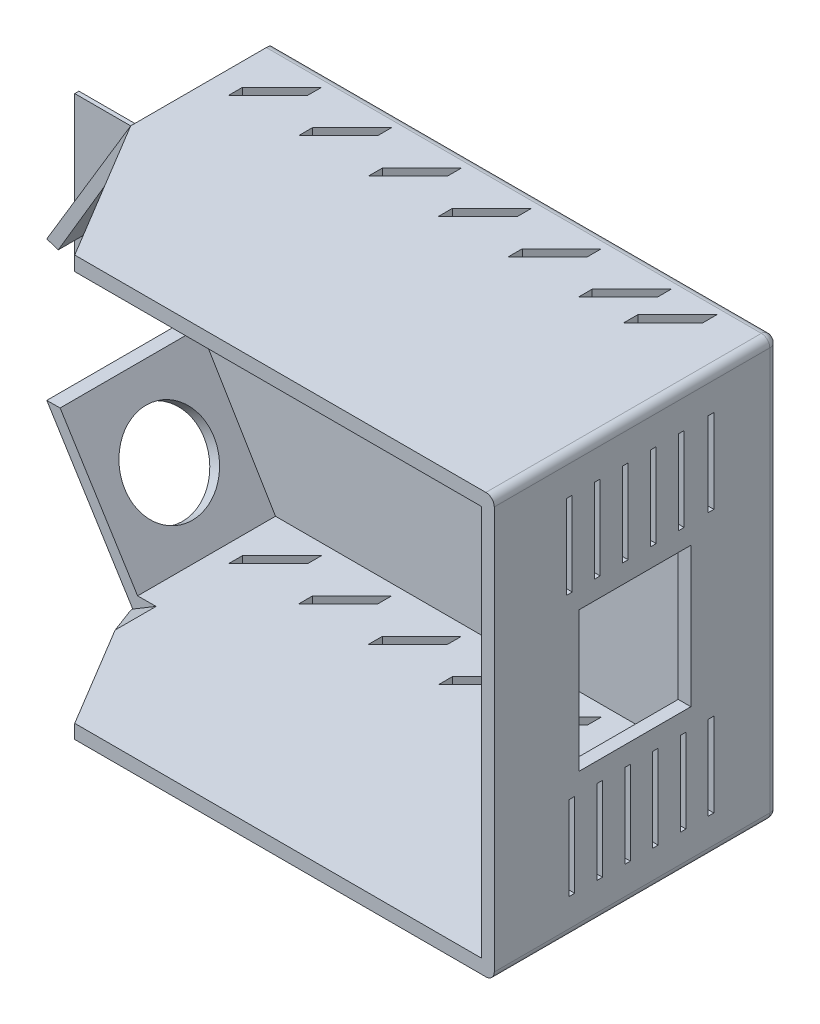
SolidWorks part; units mm, degrees
ref_plane "前视基准面" through (0, 0, 0) normal (0, 0, 1) x (1, 0, 0)
ref_plane "上视基准面" through (0, 0, 0) normal (0, 1, 0) x (1, 0, 0)
ref_plane "右视基准面" through (0, 0, 0) normal (1, 0, 0) x (0, 0, -1)
sketch "草图1" plane through (0, 0, 0) normal (0, 0, 1) x (1, 0, 0)
  line L1 (-53.7975, 24.9859) -> (196.2025, 24.9859)
  line L2 (-53.7975, 24.9859) -> (-53.7975, -125.0141)
  line L3 (-53.7975, -125.0141) -> (196.2025, -125.0141)
  line L4 (196.2025, 24.9859) -> (196.2025, -125.0141)
  dimension "D1" = 250
  dimension "D2" = 150
extrude "凸台-拉伸1" add sketch "草图1" along normal blind 1.5
sketch "草图2" plane through (0, 0, 1.5) normal (0, 0, 1) x (1, 0, 0)
  line L0 (-53.7975, -25.0141) -> (-13.7975, -25.0141)
  line L1 (-53.7975, 24.9859) -> (-53.7975, -125.0141) construction
  line L2 (-13.7975, -25.0141) -> (-13.7975, 24.9859)
  line L3 (196.2025, 24.9859) -> (-53.7975, 24.9859) construction
  line L4 (-13.7975, 24.9859) -> (-53.7975, 24.9859)
  line L5 (-53.7975, 24.9859) -> (-53.7975, -25.0141)
  dimension "D1" = 40
  dimension "D2" = 50
extrude "切除-拉伸1" cut sketch "草图2" against normal through all
sketch "草图3" plane through (0, 0, 1.5) normal (0, 0, 1) x (1, 0, 0)
  line L0 (-53.7975, -75.0141) -> (-13.7975, -75.0141)
  line L1 (-53.7975, -25.0141) -> (-53.7975, -125.0141) construction
  line L2 (-13.7975, -75.0141) -> (-13.7975, -125.0141)
  line L3 (-53.7975, -125.0141) -> (196.2025, -125.0141) construction
  line L4 (-13.7975, -125.0141) -> (-53.7975, -125.0141)
  line L5 (-53.7975, -125.0141) -> (-53.7975, -75.0141)
  dimension "D1" = 40
  dimension "D2" = 50
extrude "切除-拉伸2" cut sketch "草图3" against normal through all
sketch "草图4" plane through (0, 0, 1.5) normal (0, 0, 1) x (1, 0, 0)
  line L0 (-13.7975, -75.0141) -> (16.2025, -125.0141)
  line L1 (-13.7975, -125.0141) -> (196.2025, -125.0141) construction
  line L2 (16.2025, -125.0141) -> (-13.7975, -125.0141)
  line L3 (-13.7975, -75.0141) -> (-13.7975, -125.0141)
  line L4 (-13.7975, -25.0141) -> (16.2025, 24.9859)
  line L5 (196.2025, 24.9859) -> (-13.7975, 24.9859) construction
  line L6 (16.2025, 24.9859) -> (-13.7975, 24.9859)
  line L7 (-13.7975, 24.9859) -> (-13.7975, -25.0141)
  dimension "D1" = 30
  dimension "D2" = 30
extrude "切除-拉伸3" cut sketch "草图4" against normal through all
sketch "草图5" plane through (0, 0, 1.5) normal (0, 0, 1) x (1, 0, 0)
  line L0 (16.2025, -125.0141) -> (196.2025, -125.0141) construction
  line L1 (46.2025, -65.0141) -> (146.2025, -65.0141)
  line L2 (46.2025, -65.0141) -> (46.2025, -55.0141)
  line L3 (46.2025, -55.0141) -> (146.2025, -55.0141)
  line L4 (146.2025, -65.0141) -> (146.2025, -55.0141)
  line L6 (196.2025, -125.0141) -> (196.2025, 24.9859) construction
  line L7 (196.2025, 24.9859) -> (16.2025, 24.9859) construction
  line L8 (46.2025, -45.0141) -> (146.2025, -45.0141)
  line L9 (46.2025, -45.0141) -> (46.2025, -35.0141)
  line L10 (46.2025, -35.0141) -> (146.2025, -35.0141)
  line L11 (146.2025, -45.0141) -> (146.2025, -35.0141)
  dimension "D1" = 60
  dimension "D2" = 100
  dimension "D3" = 50
  dimension "D4" = 100
  dimension "D5" = 10
  dimension "D6" = 10
  dimension "D7" = 60
  dimension "D8" = 50
extrude "切除-拉伸4" cut sketch "草图5" against normal through all
sketch "草图6" plane through (0, 0, 1.5) normal (0, 0, 1) x (1, 0, 0)
  line L0 (-13.7975, -75.0141) -> (-9.0611, -75.0141)
  line L1 (-9.0611, -75.0141) -> (17.9752, -120.0105)
  line L2 (17.9752, -120.0105) -> (191.673, -120.0105)
  line L3 (191.673, -120.0105) -> (191.673, 24.9859)
  line L4 (196.2025, 24.9859) -> (16.2025, 24.9859) construction
  line L5 (191.673, 24.9859) -> (196.2025, 24.9859)
  line L6 (196.2025, 24.9859) -> (196.2025, -125.0141)
  line L7 (196.2025, -125.0141) -> (16.2025, -125.0141)
  line L8 (16.2025, -125.0141) -> (-13.7975, -75.0141)
extrude "凸台-拉伸2" add sketch "草图6" along normal blind 100
sketch "草图7" plane through (0, 0, 1.5) normal (0, 0, 1) x (1, 0, 0)
  line L0 (-9.7019, -26.3734) -> (17.6391, 19.8458)
  line L1 (17.6391, 19.8458) -> (191.673, 19.8458)
  line L2 (191.673, 24.9859) -> (191.673, -120.0105) construction
  line L3 (191.673, 19.8458) -> (191.673, 24.9859)
  line L4 (191.673, 24.9859) -> (16.2025, 24.9859)
  line L5 (16.2025, 24.9859) -> (-13.7975, -25.0141)
  line L6 (-13.7975, -25.0141) -> (-9.7019, -26.3734)
extrude "凸台-拉伸3" add sketch "草图7" along normal blind 100
sketch "草图8" plane through (0, 24.9859, 0) normal (0, 1, 0) x (1, 0, 0)
  line L0 (179.467, -10.1829) -> (165.3249, -24.325)
  line L1 (165.3249, -24.325) -> (165.3249, -19.325)
  line L2 (165.3249, -19.325) -> (179.467, -5.1829)
  line L3 (179.467, -5.1829) -> (179.467, -10.1829)
  line L4 (163.3997, -10.4077) -> (149.2576, -24.5498)
  line L5 (149.2576, -24.5498) -> (149.2576, -19.5498)
  line L6 (149.2576, -19.5498) -> (163.3997, -5.4077)
  line L7 (163.3997, -5.4077) -> (163.3997, -10.4077)
  line L8 (124.2576, -24.5498) -> (124.2576, -19.5498)
  line L9 (124.2576, -19.5498) -> (138.3997, -5.4077)
  line L10 (138.3997, -5.4077) -> (138.3997, -10.4077)
  line L11 (138.3997, -10.4077) -> (124.2576, -24.5498)
  line L12 (99.2576, -24.5498) -> (99.2576, -19.5498)
  line L13 (99.2576, -19.5498) -> (113.3997, -5.4077)
  line L14 (113.3997, -5.4077) -> (113.3997, -10.4077)
  line L15 (113.3997, -10.4077) -> (99.2576, -24.5498)
  line L16 (74.2576, -24.5498) -> (74.2576, -19.5498)
  line L17 (74.2576, -19.5498) -> (88.3997, -5.4077)
  line L18 (88.3997, -5.4077) -> (88.3997, -10.4077)
  line L19 (88.3997, -10.4077) -> (74.2576, -24.5498)
  line L20 (49.2576, -24.5498) -> (49.2576, -19.5498)
  line L21 (49.2576, -19.5498) -> (63.3997, -5.4077)
  line L22 (63.3997, -5.4077) -> (63.3997, -10.4077)
  line L23 (63.3997, -10.4077) -> (49.2576, -24.5498)
  line L24 (24.2576, -24.5498) -> (24.2576, -19.5498)
  line L25 (24.2576, -19.5498) -> (38.3997, -5.4077)
  line L26 (38.3997, -5.4077) -> (38.3997, -10.4077)
  line L27 (38.3997, -10.4077) -> (24.2576, -24.5498)
  dimension "D1" = 20
  dimension "D2" = 5
  dimension "D3" = 20
  dimension "D4" = 5
  dimension "D5" = 6
extrude "切除-拉伸5" cut sketch "草图8" against normal through all
sketch "草图11" plane through (-43.2396, -25.9438, 0) normal (-0.8575, -0.5145, 0) x (0, 0, 1)
  line L0 (101.5, -57.2253) -> (51.5, -57.2253)
  line L1 (101.5, -57.2253) -> (1.5, -57.2253) construction
  line L2 (51.5, -57.2253) -> (50.75, -115.5348)
  line L3 (0, -115.5348) -> (101.5, -115.5348) construction
  line L4 (50.75, -115.5348) -> (101.5, -115.5348)
  line L5 (101.5, -115.5348) -> (101.5, -57.2253)
extrude "切除-拉伸7" cut sketch "草图11" against normal blind 10
sketch "草图14" plane through (0.8904, -0.5343, 0) normal (-0.8575, 0.5145, 0) x (0, 0, 1)
  line L0 (101.5, -28.5481) -> (1.5, -28.5481) construction
  line L1 (101.5, 29.7614) -> (51.5, 29.7614)
  line L2 (101.5, 29.7614) -> (101.5, -28.5481)
  line L3 (101.5, -28.5481) -> (51.5, -28.5481)
  line L4 (51.5, 29.7614) -> (51.5, -28.5481)
extrude "切除-拉伸10" cut sketch "草图14" against normal blind 10
sketch "草图15" plane through (-43.2396, -25.9438, 0) normal (-0.8575, -0.5145, 0) x (0, 0, 1)
  line L0 (51.5, -57.2253) -> (50.75, -115.5348) construction
  line L1 (51.5, -57.2253) -> (1.5, -57.2253) construction
  circle A0 centre (26.1249, -86.2253) radius 16
  dimension "D1" = 25
  dimension "D2" = 29
extrude "切除-拉伸11" cut sketch "草图15" against normal blind 10
sketch "草图19" plane through (0, 24.9859, 0) normal (0, 1, 0) x (1, 0, 0)
  line L0 (46.2025, -101.5) -> (16.2025, -51.5)
  line L1 (196.2025, -101.5) -> (16.2025, -101.5) construction
  line L2 (16.2025, -51.5) -> (16.2025, -101.5)
  line L3 (16.2025, -101.5) -> (46.2025, -101.5)
  dimension "D1" = 30
extrude "切除-拉伸14" cut sketch "草图19" against normal through all
sketch "草图20" plane through (196.2025, 0, 0) normal (1, 0, 0) x (0, 0, -1)
  line L0 (-101.5, -125.0141) -> (0, -125.0141) construction
  line L1 (-71.2078, -75.0141) -> (-31.2078, -75.0141)
  line L2 (-71.2078, -75.0141) -> (-71.2078, -25.0141)
  line L3 (-71.2078, -25.0141) -> (-31.2078, -25.0141)
  line L4 (-31.2078, -75.0141) -> (-31.2078, -25.0141)
  dimension "D1" = 50
  dimension "D2" = 40
  dimension "D3" = 50
extrude "切除-拉伸15" cut sketch "草图20" against normal blind 10
fillet "圆角1" radius 3 5 edges at (106.2025, 24.9859, 0) (106.2025, -125.0141, 0) (196.2025, -50.0141, 0) (196.2025, -125.0141, 50.75) (196.2025, 24.9859, 50.75)
sketch "草图21" plane through (196.2025, 0, 0) normal (1, 0, 0) x (0, 0, -1)
  line L0 (-64.8006, -112.0141) -> (-62.8006, -112.0141)
  line L1 (-74.7508, -112.0141) -> (-72.7508, -112.0141)
  line L2 (-74.7508, -112.0141) -> (-74.7508, -82.0141)
  line L3 (-74.7508, -82.0141) -> (-72.7508, -82.0141)
  line L4 (-72.7508, -112.0141) -> (-72.7508, -82.0141)
  line L5 (-64.8006, -112.0141) -> (-64.8006, -82.0141)
  line L6 (-64.8006, -82.0141) -> (-62.8006, -82.0141)
  line L7 (-62.8006, -112.0141) -> (-62.8006, -82.0141)
  line L8 (-54.8505, -112.0141) -> (-52.8505, -112.0141)
  line L9 (-54.8505, -112.0141) -> (-54.8505, -82.0141)
  line L10 (-54.8505, -82.0141) -> (-52.8505, -82.0141)
  line L11 (-52.8505, -112.0141) -> (-52.8505, -82.0141)
  line L12 (-44.9003, -112.0141) -> (-42.9003, -112.0141)
  line L13 (-44.9003, -112.0141) -> (-44.9003, -82.0141)
  line L14 (-44.9003, -82.0141) -> (-42.9003, -82.0141)
  line L15 (-42.9003, -112.0141) -> (-42.9003, -82.0141)
  line L16 (-34.9502, -112.0141) -> (-32.9502, -112.0141)
  line L17 (-34.9502, -112.0141) -> (-34.9502, -82.0141)
  line L18 (-34.9502, -82.0141) -> (-32.9502, -82.0141)
  line L19 (-32.9502, -112.0141) -> (-32.9502, -82.0141)
  line L20 (-25, -112.0141) -> (-23, -112.0141)
  line L21 (-25, -112.0141) -> (-25, -82.0141)
  line L22 (-25, -82.0141) -> (-23, -82.0141)
  line L23 (-23, -112.0141) -> (-23, -82.0141)
  line L24 (-65.6261, -18.3004) -> (-63.6261, -18.3004)
  line L25 (-75.6261, -18.3004) -> (-73.6261, -18.3004)
  line L26 (-75.6261, -18.3004) -> (-75.6261, 11.6996)
  line L27 (-75.6261, 11.6996) -> (-73.6261, 11.6996)
  line L28 (-73.6261, -18.3004) -> (-73.6261, 11.6996)
  line L29 (-65.6261, -18.3004) -> (-65.6261, 11.6996)
  line L30 (-65.6261, 11.6996) -> (-63.6261, 11.6996)
  line L31 (-63.6261, -18.3004) -> (-63.6261, 11.6996)
  line L32 (-55.6261, -18.3004) -> (-53.6261, -18.3004)
  line L33 (-55.6261, -18.3004) -> (-55.6261, 11.6996)
  line L34 (-55.6261, 11.6996) -> (-53.6261, 11.6996)
  line L35 (-53.6261, -18.3004) -> (-53.6261, 11.6996)
  line L36 (-45.6261, -18.3004) -> (-43.6261, -18.3004)
  line L37 (-45.6261, -18.3004) -> (-45.6261, 11.6996)
  line L38 (-45.6261, 11.6996) -> (-43.6261, 11.6996)
  line L39 (-43.6261, -18.3004) -> (-43.6261, 11.6996)
  line L40 (-35.6261, -18.3004) -> (-33.6261, -18.3004)
  line L41 (-35.6261, -18.3004) -> (-35.6261, 11.6996)
  line L42 (-35.6261, 11.6996) -> (-33.6261, 11.6996)
  line L43 (-33.6261, -18.3004) -> (-33.6261, 11.6996)
  line L44 (-25, -18.0141) -> (-23, -18.0141)
  line L45 (-25, -18.0141) -> (-25, 11.9859)
  line L46 (-25, 11.9859) -> (-23, 11.9859)
  line L47 (-23, -18.0141) -> (-23, 11.9859)
  line L48 (-3, -122.0141) -> (-3, 21.9859) construction
  line L49 (-101.5, -122.0141) -> (-3, -122.0141) construction
  line L50 (-3, 21.9859) -> (-101.5, 21.9859) construction
  dimension "D1" = 2
  dimension "D2" = 30
  dimension "D4" = 2
  dimension "D5" = 30
  dimension "D6" = 20
  dimension "D7" = 20
  dimension "D8" = 10
  dimension "D9" = 10
  dimension "D3" = 6
extrude "切除-拉伸16" cut sketch "草图21" against normal blind 10
